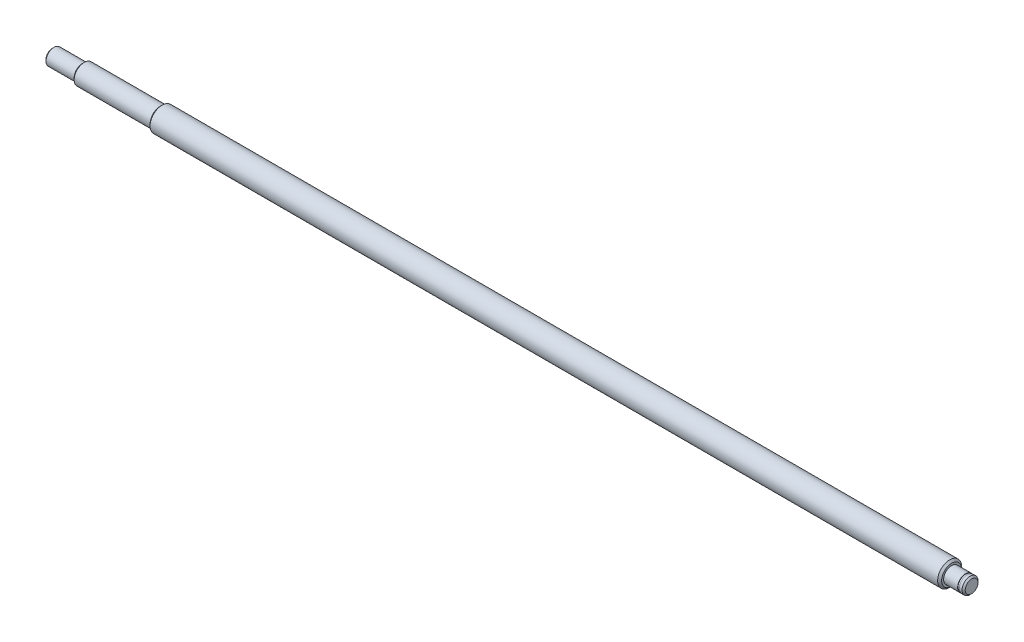
SolidWorks part; units mm, degrees
material "1.4057 (X17CrNi16-2)"
ref_plane "Plan de face" through (0, 0, 0) normal (0, 0, 1) x (1, 0, 0)
ref_plane "Plan de dessus" through (0, 0, 0) normal (0, 1, 0) x (1, 0, 0)
ref_plane "Plan de droite" through (0, 0, 0) normal (1, 0, 0) x (0, 0, -1)
sketch "Esquisse1" plane through (0, 0, 0) normal (0, 0, 1) x (1, 0, 0)
  line L0 (-511.9709, 0) -> (511.9709, 0) construction
  line L1 (-250, 0) -> (-250, 3.2)
  line L2 (-249.2, 4) -> (-235, 4)
  line L3 (-235, 4) -> (-235, 4.1)
  line L4 (-234.1, 5) -> (-196, 5)
  line L5 (-196, 5) -> (-196, 5.1)
  line L6 (-195.1, 6) -> (199, 6)
  line L7 (-250, 3.2) -> (-249.2, 4)
  line L8 (200, 5) -> (200, 4)
  line L9 (200, 4) -> (207, 4)
  line L10 (210, 3.2) -> (210, 0)
  line L11 (207, 4) -> (207, 3.8)
  line L12 (207, 3.8) -> (207.9, 3.8)
  line L13 (207.9, 3.8) -> (207.9, 4)
  line L14 (207.9, 4) -> (209.2, 4)
  line L15 (209.2, 4) -> (210, 3.2)
  line L16 (199, 6) -> (200, 5)
  line L17 (-196, 5.1) -> (-195.1, 6)
  line L18 (-235, 4.1) -> (-234.1, 5)
  line L19 (-250, 0) -> (210, 0)
  point P4 (0, 0)
  point P6 (-250, 4)
  point P7 (200, 6)
  point P9 (-235, 5)
  point P11 (-196, 6)
  point P14 (210, 4)
  point P28 (-250, 1.6)
  dimension "D1" = 4
  dimension "D2" = 5
  dimension "D3" = 6
  dimension "D4" = 0.8
  dimension "D5" = 45
  dimension "D6" = 15
  dimension "D7" = 39
  dimension "D8" = 4
  dimension "D9" = 10
  dimension "D10" = 7
  dimension "D11" = 0.9
  dimension "D12" = 0.2
  dimension "D13" = 0.8
  dimension "D14" = 45
  dimension "D15" = 1
  dimension "D16" = 45
  dimension "D17" = 0.9
  dimension "D18" = 45
  dimension "D19" = 0.9
  dimension "D20" = 45
  dimension "D21" = 460
  dimension "D22" = 250
revolve "Révolution1" add sketch "Esquisse1" angle 360 about L0
